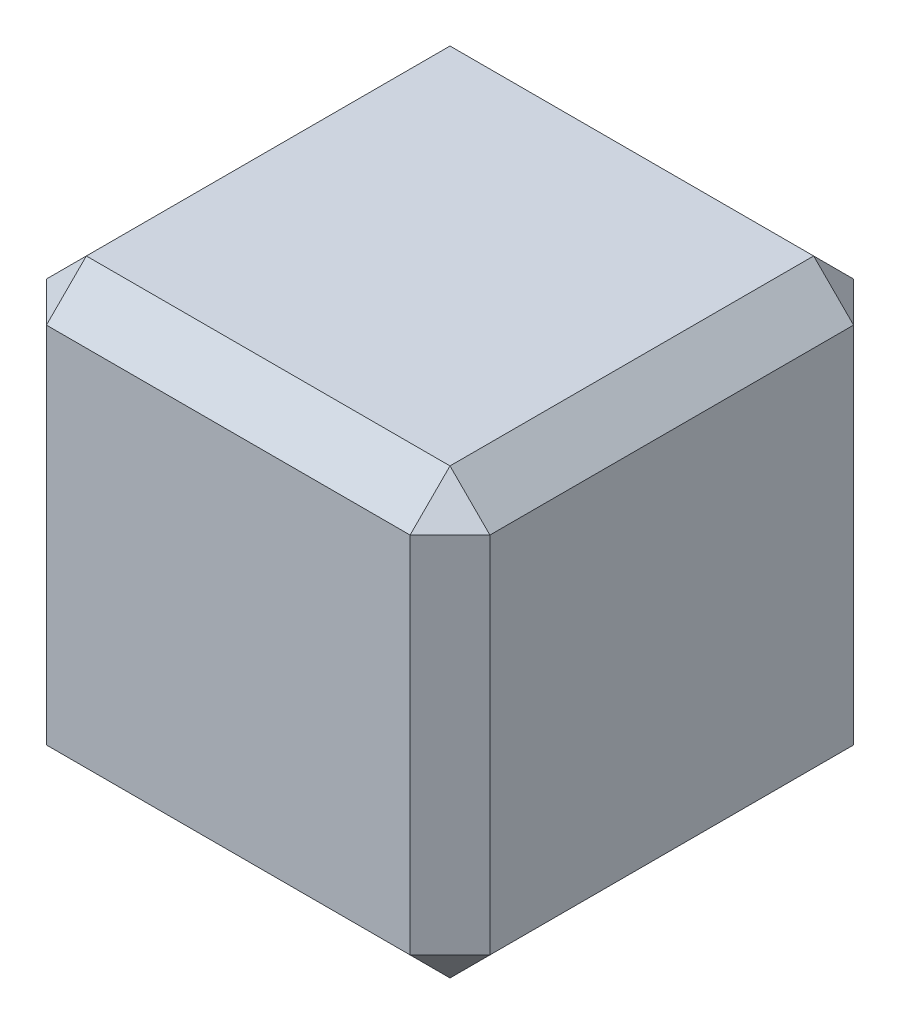
SolidWorks part; units mm, degrees
ref_plane "前视基准面" through (0, 0, 0) normal (0, 0, 1) x (1, 0, 0)
ref_plane "上视基准面" through (0, 0, 0) normal (0, 1, 0) x (1, 0, 0)
ref_plane "右视基准面" through (0, 0, 0) normal (1, 0, 0) x (0, 0, -1)
sketch "草图1" plane through (0, 0, 0) normal (0, 0, 1) x (1, 0, 0)
  line L1 (-100, -100) -> (100, -100)
  line L2 (-100, -100) -> (-100, 100)
  line L3 (-100, 100) -> (100, 100)
  line L4 (100, -100) -> (100, 100)
  line L5 (0, 100) -> (0, -100) construction
  line L6 (-100, 0) -> (100, 0) construction
  point P0 (0, 0)
  dimension "D1" = 200
extrude "凸台-拉伸1" add sketch "草图1" along normal mid plane 200
chamfer "倒角1" distance 18 angle 45 12 edges at (100, 100, 0) (0, 100, 100) (100, 0, 100) (-100, 100, 0) (-100, -100, 0) (-100, 0, 100) (0, -100, 100) (100, -100, 0) (0, -100, -100) (-100, 0, -100) (0, 100, -100) (100, 0, -100)
